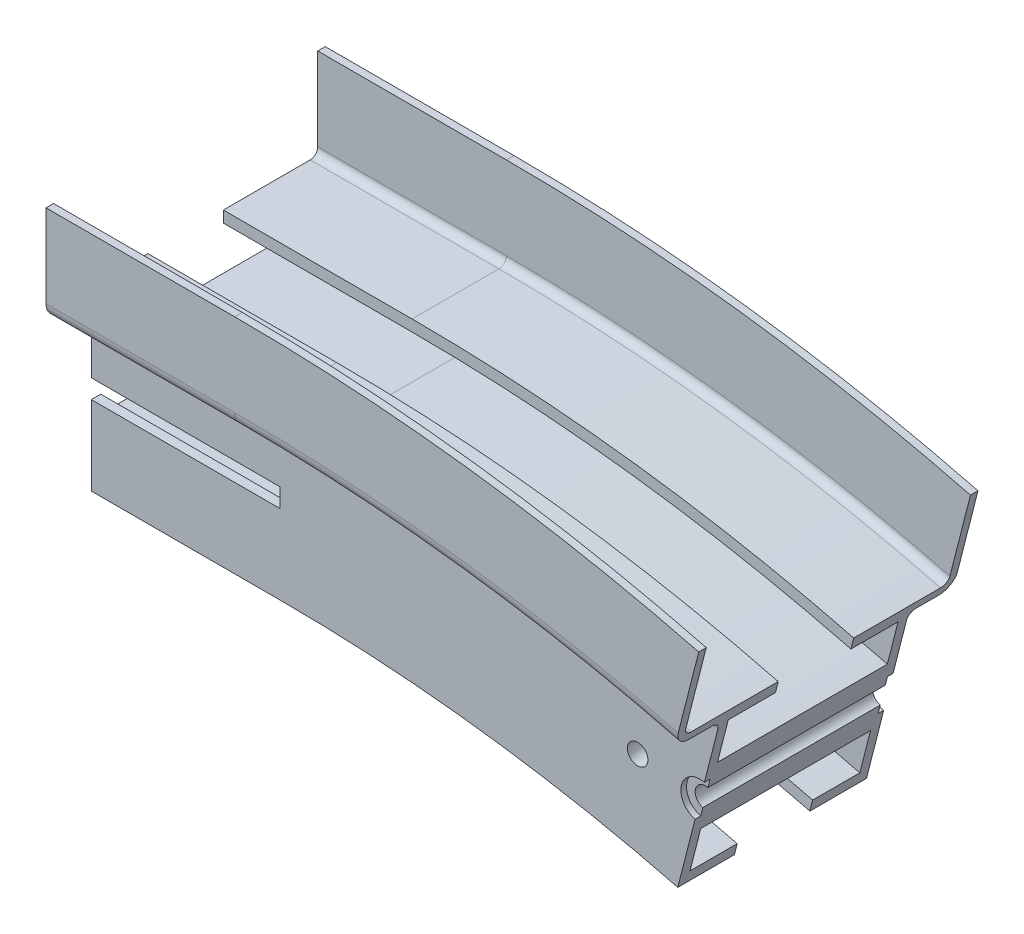
SolidWorks part; units mm, degrees
material "ABS generico"
ref_plane "Piano frontale" through (0, 0, 0) normal (0, 0, 1) x (1, 0, 0)
ref_plane "Piano superiore" through (0, 0, 0) normal (0, 1, 0) x (1, 0, 0)
ref_plane "Piano destro" through (0, 0, 0) normal (1, 0, 0) x (0, 0, -1)
sketch "Schizzo1" plane through (0, 0, 0) normal (1, 0, 0) x (0, 0, -1)
  line L0 (-10, -23.5) -> (-10, -20.5)
  line L1 (-10, -20.5) -> (-22.5, -20.5)
  line L2 (-22.5, -20.5) -> (-22.5, -9)
  line L3 (-22.5, -9) -> (22.5, -9)
  line L4 (22.5, -9) -> (22.5, -20.5)
  line L5 (22.5, -20.5) -> (10, -20.5)
  line L6 (10, -20.5) -> (10, -23.5)
  line L7 (10, -23.5) -> (25, -23.5)
  line L8 (25, -23.5) -> (25, -2.5)
  line L9 (27, 21.5) -> (33, 21.5)
  line L10 (37, 25.5) -> (37, 47.5)
  line L11 (37, 47.5) -> (35, 47.5)
  line L12 (35, 47.5) -> (35, 25.5)
  line L13 (33, 23.5) -> (10, 23.5)
  line L14 (10, 23.5) -> (10, 20.5)
  line L15 (10, 20.5) -> (22.5, 20.5)
  line L16 (22.5, 20.5) -> (22.5, 9)
  line L17 (22.5, 9) -> (-22.5, 9)
  line L18 (-22.5, 9) -> (-22.5, 20.5)
  line L19 (-22.5, 20.5) -> (-10, 20.5)
  line L20 (-10, 20.5) -> (-10, 23.5)
  line L21 (-10, 23.5) -> (-33, 23.5)
  line L22 (-35, 25.5) -> (-35, 47.5)
  line L23 (-35, 47.5) -> (-37, 47.5)
  line L24 (-37, 47.5) -> (-37, 25.5)
  line L25 (-33, 21.5) -> (-27, 21.5)
  line L26 (-25, 19.5) -> (-25, 2.5)
  line L27 (-25, -23.5) -> (-10, -23.5)
  line L28 (-12.5, 0) -> (-25, 0) construction
  line L29 (-22.5, 7) -> (-12.5, 7)
  line L30 (-22.5, 7) -> (-22.5, 2.5)
  line L31 (-22.5, -7) -> (-12.5, -7)
  line L32 (-12.5, 7) -> (-12.5, -7)
  line L33 (-12.5, 0) -> (12.5, 0) construction
  line L34 (12.5, 7) -> (22.5, 7)
  line L35 (12.5, 7) -> (12.5, -7)
  line L36 (12.5, -7) -> (22.5, -7)
  line L37 (22.5, 7) -> (22.5, 2.5)
  line L38 (-25, 2.5) -> (-22.5, 2.5)
  line L39 (-8.5, 7) -> (8.5, 7)
  line L40 (-10, 5.5) -> (-10, -5.5)
  line L41 (-8.5, -7) -> (8.5, -7)
  line L42 (10, 5.5) -> (10, -5.5)
  line L43 (-25, -2.5) -> (-22.5, -2.5)
  line L44 (-22.5, -2.5) -> (-22.5, -7)
  line L45 (22.5, 2.5) -> (25, 2.5)
  line L46 (22.5, -2.5) -> (25, -2.5)
  line L47 (22.5, -2.5) -> (22.5, -7)
  line L48 (-25, -2.5) -> (-25, -23.5)
  line L49 (25, 2.5) -> (25, 19.5)
  line L50 (12.5, 0) -> (25, 0) construction
  line L51 (-25, -2.5) -> (-25, 2.5) construction
  line L52 (25, -2.5) -> (25, 2.5) construction
  arc A0 (-27, 21.5) -> (-25, 19.5) centre (-27, 19.5) cw
  arc A1 (-37, 25.5) -> (-33, 21.5) centre (-33, 25.5) ccw
  arc A2 (-35, 25.5) -> (-33, 23.5) centre (-33, 25.5) ccw
  arc A3 (33, 23.5) -> (35, 25.5) centre (33, 25.5) ccw
  arc A4 (37, 25.5) -> (33, 21.5) centre (33, 25.5) cw
  arc A5 (25, 19.5) -> (27, 21.5) centre (27, 19.5) cw
  arc A6 (-8.5, -7) -> (-10, -5.5) centre (-8.5, -5.5) cw
  arc A7 (8.5, -7) -> (10, -5.5) centre (8.5, -5.5) ccw
  arc A8 (10, 5.5) -> (8.5, 7) centre (8.5, 5.5) ccw
  arc A9 (-8.5, 7) -> (-10, 5.5) centre (-8.5, 5.5) ccw
  point P57 (-10, 0)
  point P74 (0, 0)
  point P76 (-22.5, -4.75)
  dimension "D10" = 4
  dimension "D11" = 2
  dimension "D19" = 1.5
  dimension "D1" = 50
  dimension "D2" = 18
  dimension "D3" = 21
  dimension "D4" = 15
  dimension "D5" = 3
  dimension "D6" = 4.5
  dimension "D7" = 11.5
  dimension "D8" = 19
  dimension "D9" = 45
  dimension "D12" = 74
  dimension "D13" = 2
  dimension "D14" = 24
  dimension "D15" = 27
  dimension "D16" = 2.5
  dimension "D17" = 2.5
  dimension "D18" = 2.5
  dimension "D20" = 2.5
  dimension "D21" = 2.5
  dimension "D22" = 2.5
  dimension "D23" = 10
extrude "Estrusione-Estrusione1" add sketch "Schizzo1" along normal blind 50
chamfer "Smusso1" distance 1.6 angle 45 8 edges at (25, 7, -12.5) (25, 7, -22.5) (25, -7, -22.5) (25, -7, -12.5) (25, -7, 22.5) (25, 7, 22.5) (25, 7, 12.5) (25, -7, 12.5)
sketch "Schizzo2" plane through (50, 0, 0) normal (1, 0, 0) x (0, 0, -1)
  line L0 (-10, -23.5) -> (-25, -23.5)
  line L1 (-25, -23.5) -> (-25, 19.5)
  line L2 (-10, -23.5) -> (-10, -20.5)
  line L3 (-10, -20.5) -> (-22.5, -20.5)
  line L4 (-22.5, -20.5) -> (-22.5, -9)
  line L5 (-22.5, -9) -> (22.5, -9)
  line L6 (22.5, -9) -> (22.5, -20.5)
  line L7 (22.5, -20.5) -> (10, -20.5)
  line L8 (10, -20.5) -> (10, -23.5)
  line L9 (10, -23.5) -> (25, -23.5)
  line L10 (25, -23.5) -> (25, 19.5)
  line L11 (27, 21.5) -> (33, 21.5)
  line L12 (37, 25.5) -> (37, 47.5)
  line L13 (37, 47.5) -> (35, 47.5)
  line L14 (35, 47.5) -> (35, 25.5)
  line L15 (33, 23.5) -> (10, 23.5)
  line L16 (10, 23.5) -> (10, 20.5)
  line L17 (10, 23.5) -> (10, 20.5) construction
  line L18 (10, 20.5) -> (22.5, 20.5) construction
  line L19 (10, 20.5) -> (22.5, 20.5)
  line L20 (22.5, 20.5) -> (22.5, 9)
  line L21 (22.5, 9) -> (-22.5, 9)
  line L22 (-22.5, 9) -> (-22.5, 20.5)
  line L23 (-22.5, 20.5) -> (-10, 20.5)
  line L24 (-10, 20.5) -> (-10, 23.5)
  line L25 (-10, 23.5) -> (-33, 23.5)
  line L26 (-35, 25.5) -> (-35, 47.5)
  line L27 (-35, 47.5) -> (-37, 47.5)
  line L28 (-37, 47.5) -> (-37, 25.5)
  line L29 (-37, 47.5) -> (-37, 25.5) construction
  line L30 (-33, 21.5) -> (-27, 21.5)
  line L31 (-89.8861, -450) -> (122.001, -450) construction
  line L32 (-25, 0) -> (25, 0) construction
  arc A0 (25, 19.5) -> (27, 21.5) centre (27, 19.5) cw
  arc A1 (33, 21.5) -> (37, 25.5) centre (33, 25.5) ccw
  arc A2 (33, 21.5) -> (37, 25.5) centre (33, 25.5) ccw construction
  arc A3 (35, 25.5) -> (33, 23.5) centre (33, 25.5) cw
  arc A4 (-33, 23.5) -> (-35, 25.5) centre (-33, 25.5) cw
  arc A5 (-37, 25.5) -> (-33, 21.5) centre (-33, 25.5) ccw construction
  arc A6 (-37, 25.5) -> (-33, 21.5) centre (-33, 25.5) ccw
  arc A7 (-27, 21.5) -> (-25, 19.5) centre (-27, 19.5) cw
  dimension "D1" = 450
revolve "Rivoluzione1" add sketch "Schizzo2" angle 14.31 about L31
sketch "Schizzo7" plane through (154.72, -39.4664, 0) normal (0.969, -0.2472, 0) x (0, 0, 1)
  line L0 (25, -8.3207) -> (-25, -8.3207) construction
  line L1 (25, -45.8207) -> (25, -2.8207) construction
  line L2 (-25, -2.8207) -> (-25, -45.8207) construction
  line L3 (22.5, -17.3207) -> (-22.5, -17.3207) construction
  dimension "D1" = 9
sketch "Schizzo18" plane through (154.72, -39.4664, 0) normal (0.969, -0.2472, 0) x (0, 0, 1)
  line L0 (25, -26.3207) -> (-25, -26.3207)
  line L1 (-25, -26.3207) -> (-25, -21.3207)
  line L4 (-23.5, -21.3207) -> (-23.5, -23.6207)
  line L5 (-23.5, -23.6207) -> (23.5, -23.6207)
  line L6 (23.5, -23.6207) -> (23.5, -21.3207)
  line L7 (23.5, -21.3207) -> (25, -21.3207)
  line L9 (25, -21.3207) -> (25, -26.3207)
  line L11 (-25, -21.3207) -> (-23.5, -21.3207)
  line L12 (22.5, -17.3207) -> (-22.5, -17.3207) construction
  line L13 (-25, -2.8207) -> (-25, -45.8207) construction
  line L14 (25, -45.8207) -> (25, -2.8207) construction
  dimension "D1" = 2.7
  dimension "D2" = 5
  dimension "D3" = 1.5
  dimension "D4" = 9
revolve "Taglia-Rivoluzione1" cut sketch "Schizzo18" angle 360 about L0
ref_plane "Piano7" through (0, -13.9623, 0) normal (0, 1, 0) x (1, 0, 0)
ref_plane "Piano8" through (0, -73.9623, 0) normal (0, 1, 0) x (1, 0, 0)
sketch "Schizzo24" plane through (0, -73.9623, 0) normal (0, 1, 0) x (1, 0, 0)
  line L0 (161.2257, 25) -> (161.2257, -150) construction
  circle A0 centre (161.2257, -150) radius 75
  dimension "D2" = 150
  dimension "D1" = 175
curve "Elica/Spirale3" pitch 120 height 90 turns 0.75
sketch3d "Schizzo3D2"
  line L0 (161.2257, -73.9623, 150) -> (161.2257, 61.2338, 150) construction
  line L1 (161.2257, -73.9623, 150) -> (161.2257, -73.9623, 104.4695) construction
  line L2 (161.2257, -73.9623, 150) -> (143.2021, -73.9623, 13.0977) construction
  line L3 (151.4362, -11.4623, 75.6417) -> (161.2257, -11.4623, 150) construction
  line L4 (151.4362, -11.4623, 75.6417) -> (131.8573, -11.4623, -73.0751) construction
  line L5 (107.0711, -11.4623, -69.8119) -> (156.6434, -11.4623, -76.3382) construction
  spline S0 degree 3 poles (161.2257, -73.9623, 225) (165.2839, -72.9289, 225) (173.4148, -70.8584, 224.3384) (185.2784, -67.7556, 221.3875) (196.5114, -64.6519, 216.5557) (206.8139, -61.5485, 209.9703) (215.9155, -58.4451, 201.8049) (223.5761, -55.3416, 192.2747) (229.594, -52.2382, 181.6306) (233.8106, -49.1347, 170.1531) (236.1149, -46.0313, 158.1447) (236.446, -42.9278, 145.9217) (234.7953, -39.8244, 133.8061) (231.2062, -36.7209, 122.1172) (225.7734, -33.6175, 111.1629) (218.6399, -30.5141, 101.2319) (209.9938, -27.4106, 92.5857) (200.0627, -24.3072, 85.4523) (189.1085, -21.2037, 80.0195) (177.4196, -18.1003, 76.4304) (165.304, -14.9968, 74.7797) (153.081, -11.8934, 75.1108) (141.0725, -8.7899, 77.415) (129.5951, -5.6865, 81.6316) (118.951, -2.583, 87.6495) (109.4207, 0.5204, 95.3102) (101.2553, 3.6239, 104.4118) (94.67, 6.7273, 114.7143) (89.8382, 9.8309, 125.9473) (86.8872, 12.9337, 137.8109) (86.2257, 15.0043, 145.9418) (86.2257, 16.0377, 150) knots 0 0 0 0 0.034483 0.068966 0.103448 0.137931 0.172414 0.206897 0.241379 0.275862 0.310345 0.344828 0.37931 0.413793 0.448276 0.482759 0.517241 0.551724 0.586207 0.62069 0.655172 0.689655 0.724138 0.758621 0.793103 0.827586 0.862069 0.896552 0.931034 0.965517 1 1 1 1 construction
  point P12 (131.8573, -11.4623, -73.0751)
  dimension "D1" = 7.5
  dimension "D2" = 150
  dimension "D3" = 50
ref_plane "Piano9" through (-7.2101, 0, -54.7665) normal (0.1305, 0, 0.9914) x (0.9914, 0, -0.1305)
hole_wizard "Foro per Vite M5-1" positions "Schizzo25" profile "Schizzo26" hole size "M5" standard "ISO"
sketch "Schizzo25" plane through (-7.2101, 0, -54.7665) normal (0.1305, 0, 0.9914) x (0.9914, 0, -0.1305)
  point P0 (140.2674, -11.4623)
sketch "Schizzo26" plane through (131.8573, -11.4623, -73.0751) normal (0, 1, 0) x (-0.9914, 0, 0.1305)
  line L0 (0, 0) -> (0, 161.6223)
  line L1 (0, 161.6223) -> (2.7, 160)
  line L2 (2.7, 160) -> (2.7, 0)
  line L5 (2.7, 0) -> (0, 0)
  line L10 (0, 161.6223) -> (-2.7, 160) construction
  line L11 (0, -6.35) -> (0, 107.95) construction
  dimension "Hole Dia." = 5.4
  dimension "Hole Depth" = 160
  dimension "Drill Angle" = 118
